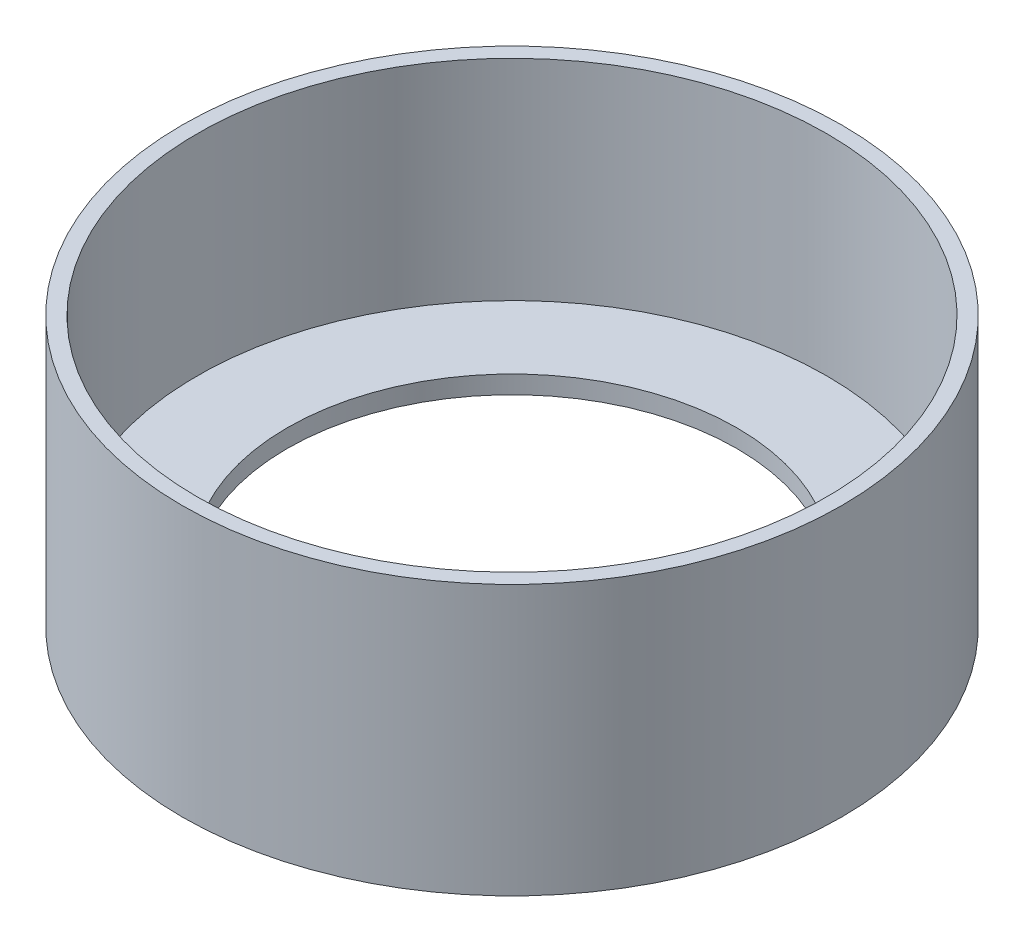
SolidWorks part; units mm, degrees
ref_plane "Front Plane" through (0, 0, 0) normal (0, 0, 1) x (1, 0, 0)
ref_plane "Top Plane" through (0, 0, 0) normal (0, 1, 0) x (1, 0, 0)
ref_plane "Right Plane" through (0, 0, 0) normal (1, 0, 0) x (0, 0, -1)
sketch "Sketch1" plane through (0, 0, 0) normal (0, 1, 0) x (1, 0, 0)
  circle A0 centre (0, 0) radius 105
  circle A1 centre (0, 0) radius 120
extrude "Boss-Extrude1" add sketch "Sketch1" along normal blind 70 and the other way blind 20
sketch "Sketch2" plane through (0, 0, 0) normal (0, 1, 0) x (1, 0, 0)
  circle A0 centre (0, 0) radius 105
  circle A1 centre (0, 0) radius 75
extrude "Boss-Extrude2" add sketch "Sketch2" against normal blind 6
sketch "Sketch3" plane through (0, 70, 0) normal (0, 1, 0) x (1, 0, 0)
  circle A0 centre (0, 0) radius 120 construction
  circle A1 centre (0, 0) radius 120
  circle A2 centre (0, 0) radius 115
  dimension "D1" = 5
extrude "Cut-Extrude1" cut sketch "Sketch3" against normal through all
sketch "Sketch4" plane through (0, 70, 0) normal (0, 1, 0) x (1, 0, 0)
  circle A3 centre (0, 0) radius 110
  circle A4 centre (0, 0) radius 110
  circle A6 centre (0, 0) radius 120
  circle A7 centre (0, 0) radius 120
  dimension "D1" = 5
  dimension "D2" = 5
extrude "Cut-Extrude2" cut sketch "Sketch4" against normal through all
